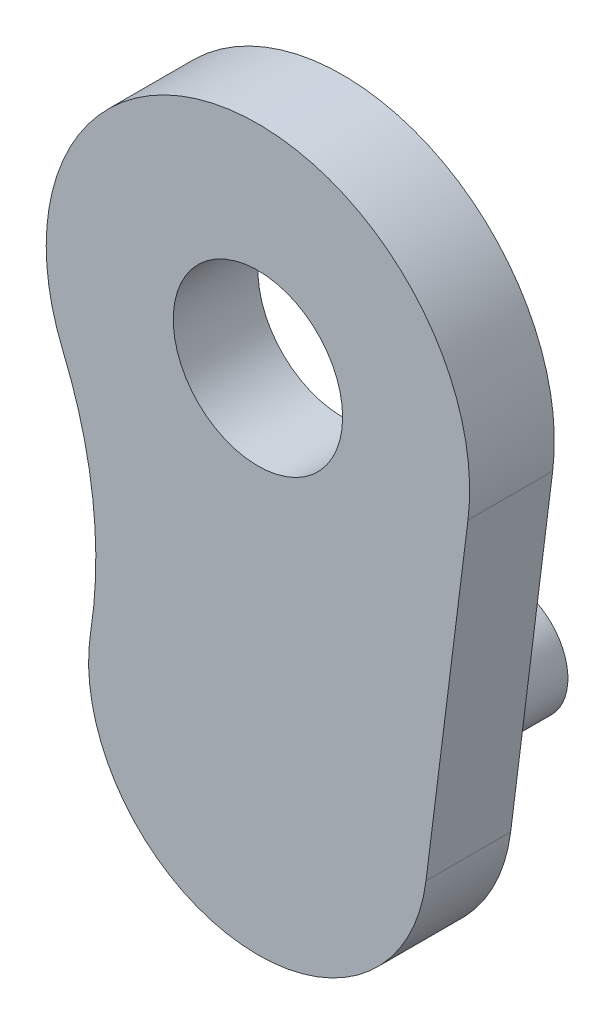
SolidWorks part; units mm, degrees
ref_plane "前视基准面" through (0, 0, 0) normal (0, 0, 1) x (1, 0, 0)
ref_plane "上视基准面" through (0, 0, 0) normal (0, 1, 0) x (1, 0, 0)
ref_plane "右视基准面" through (0, 0, 0) normal (1, 0, 0) x (0, 0, -1)
sketch "草图1" plane through (0, 0, 0) normal (0, 0, 1) x (1, 0, 0)
  line L0 (24.8039, -3.125) -> (19.8431, -42.5)
  arc A4 (24.8039, -3.125) -> (-23.0467, -9.6875) centre (0, 0) ccw
  arc A5 (-19.7544, -36.875) -> (19.8431, -42.5) centre (0, -40) ccw
  arc A6 (-23.0467, -9.6875) -> (-19.7544, -36.875) centre (-69.1402, -29.0625) cw
  circle A8 centre (0, 0) radius 10
  circle A9 centre (0, 0) radius 10 construction
  dimension "D1" = 40
  dimension "D2" = 20
  dimension "D3" = 25
  dimension "D4" = 50
extrude "凸台-拉伸1" add sketch "草图1" along normal blind 10
sketch "草图2" plane through (0, 0, 0) normal (0, 0, -1) x (-1, 0, 0)
  circle A0 centre (0, -43.432) radius 6.5998
extrude "凸台-拉伸2" add sketch "草图2" along normal blind 20
